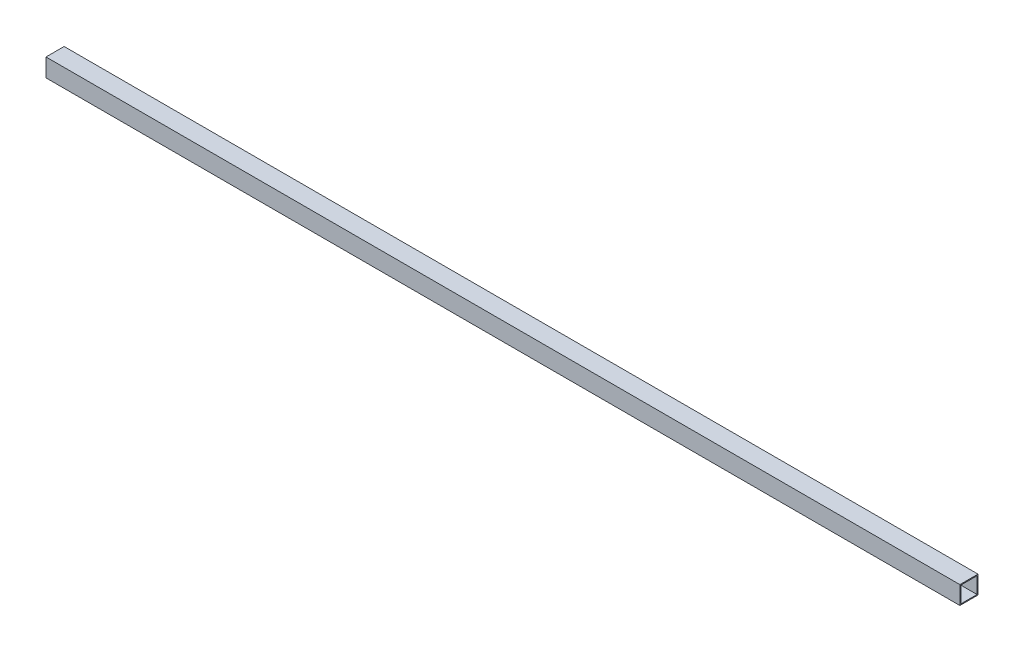
SolidWorks part; units mm, degrees
material "6063-O, Extruded Rod (SS)"
ref_plane "Front Plane" through (0, 0, 0) normal (0, 0, 1) x (1, 0, 0)
ref_plane "Top Plane" through (0, 0, 0) normal (0, 1, 0) x (1, 0, 0)
ref_plane "Right Plane" through (0, 0, 0) normal (1, 0, 0) x (0, 0, -1)
sketch "Sketch1" plane through (0, 0, 0) normal (1, 0, 0) x (0, 0, -1)
  line L0 (-8.525, 8.525) -> (8.525, 8.525)
  line L1 (-9.525, 9.525) -> (9.525, 9.525)
  line L2 (-9.525, 9.525) -> (-9.525, -9.525)
  line L3 (-9.525, -9.525) -> (9.525, -9.525)
  line L4 (9.525, 9.525) -> (9.525, -9.525)
  line L5 (-9.525, 9.525) -> (9.525, -9.525) construction
  line L6 (-9.525, -9.525) -> (9.525, 9.525) construction
  line L7 (8.525, 8.525) -> (8.525, -8.525)
  line L8 (-8.525, -8.525) -> (8.525, -8.525)
  line L9 (-8.525, 8.525) -> (-8.525, -8.525)
  point P0 (0, 0)
  dimension "D1" = 19.05
  dimension "D2" = 19.05
  dimension "D3" = 1
extrude "Boss-Extrude1" add sketch "Sketch1" along normal blind 960
